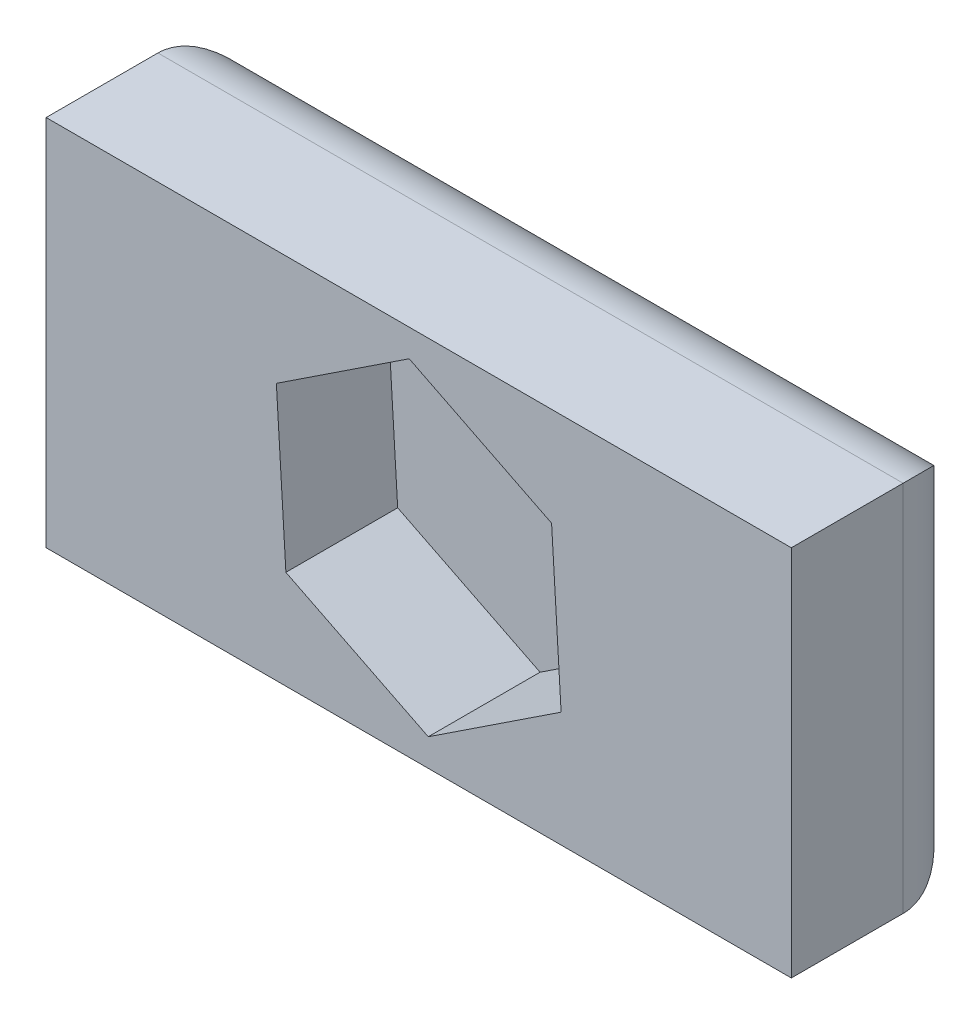
SolidWorks part; units mm, degrees
ref_plane "Front Plane" through (0, 0, 0) normal (0, 0, 1) x (1, 0, 0)
ref_plane "Top Plane" through (0, 0, 0) normal (0, 1, 0) x (1, 0, 0)
ref_plane "Right Plane" through (0, 0, 0) normal (1, 0, 0) x (0, 0, -1)
sketch "Sketch1" plane through (0, 0, 0) normal (0, 0, 1) x (1, 0, 0)
  line L1 (-10, -5) -> (10, -5)
  line L2 (-10, -5) -> (-10, 5)
  line L3 (-10, 5) -> (10, 5)
  line L4 (10, -5) -> (10, 5)
  line L5 (-10, -5) -> (10, 5) construction
  line L6 (-10, 5) -> (10, -5) construction
  point P0 (0, 0)
  dimension "D1" = 10
  dimension "D2" = 20
extrude "Boss-Extrude1" add sketch "Sketch1" along normal blind 5
sketch "Sketch2" plane through (0, 0, 5) normal (0, 0, 1) x (1, 0, 0)
  line L0 (-10, 5) -> (10, -5) construction
  line L2 (0.256, -4.2647) -> (3.8213, -1.9107)
  line L3 (3.8213, -1.9107) -> (3.5654, 2.354)
  line L4 (3.5654, 2.354) -> (-0.256, 4.2647)
  line L5 (-0.256, 4.2647) -> (-3.8213, 1.9107)
  line L6 (-3.8213, 1.9107) -> (-3.5654, -2.354)
  line L7 (-3.5654, -2.354) -> (0.256, -4.2647)
  circle A0 centre (0, 0) radius 3.7 construction
  dimension "D1" = 7.4
extrude "Cut-Extrude1" cut sketch "Sketch2" against normal blind 3
fillet "Fillet1" radius 2 4 edges at (0, 5, 0) (-10, 0, 0) (0, -5, 0) (10, 0, 0)
